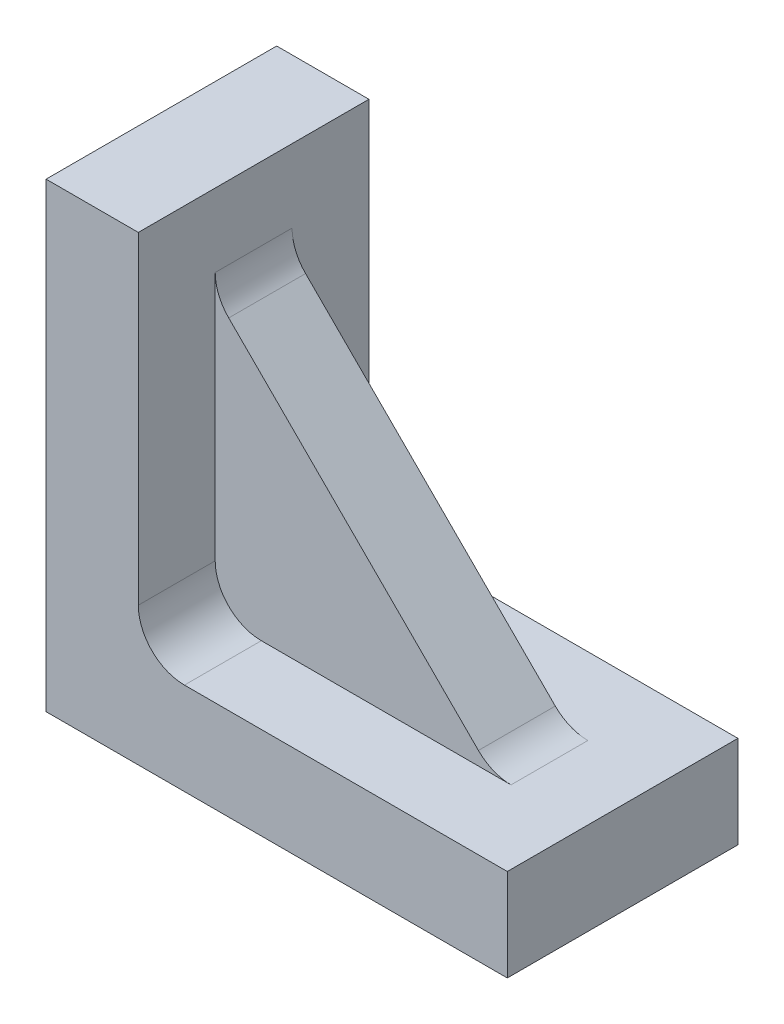
SolidWorks part; units mm, degrees
ref_plane "Front Plane" through (0, 0, 0) normal (0, 0, 1) x (1, 0, 0)
ref_plane "Top Plane" through (0, 0, 0) normal (0, 1, 0) x (1, 0, 0)
ref_plane "Right Plane" through (0, 0, 0) normal (1, 0, 0) x (0, 0, -1)
sketch "Sketch1" plane through (0, 0, 0) normal (0, 0, 1) x (1, 0, 0)
  line L0 (0, 0) -> (0, 25.4)
  line L1 (0, 0) -> (25.4, 0)
  line L2 (20.32, 5.08) -> (5.08, 20.32)
  line L3 (0, 25.4) -> (5.08, 25.4)
  line L4 (5.08, 25.4) -> (5.08, 20.32)
  line L5 (25.4, 0) -> (25.4, 5.08)
  line L6 (25.4, 5.08) -> (20.32, 5.08)
  dimension "D1" = 25.4
  dimension "D2" = 25.4
  dimension "D3" = 5.08
  dimension "D4" = 5.08
extrude "Boss-Extrude1" add sketch "Sketch1" along normal blind 12.7
sketch "Sketch3" plane through (25.4, 0, 0) normal (1, 0, 0) x (0, 0, -1)
  line L0 (-8.4667, 20.32) -> (-8.4667, 5.08)
  line L1 (-12.7, 20.32) -> (-8.4667, 20.32)
  line L2 (-12.7, 20.32) -> (-12.7, 5.08)
  line L3 (-12.7, 5.08) -> (-8.4667, 5.08)
  line L4 (0, 20.32) -> (0, 5.08)
  line L5 (-4.2333, 20.32) -> (-4.2333, 5.08)
  line L6 (-4.2333, 20.32) -> (0, 20.32)
  line L7 (-4.2333, 5.08) -> (0, 5.08)
  dimension "D1" = 4.2333
  dimension "D2" = 4.2333
extrude "Cut-Extrude1" cut sketch "Sketch3" against normal blind 20.32
fillet "Fillet1" radius 2.54 2 edges at (5.08, 5.08, 2.1167) (5.08, 5.08, 10.5833)
fillet "Fillet2" radius 2.54 2 edges at (20.32, 5.08, 6.35) (5.08, 20.32, 6.35)
scale "Scale1" scale about centroid uniform scaling yes scale factor 3
